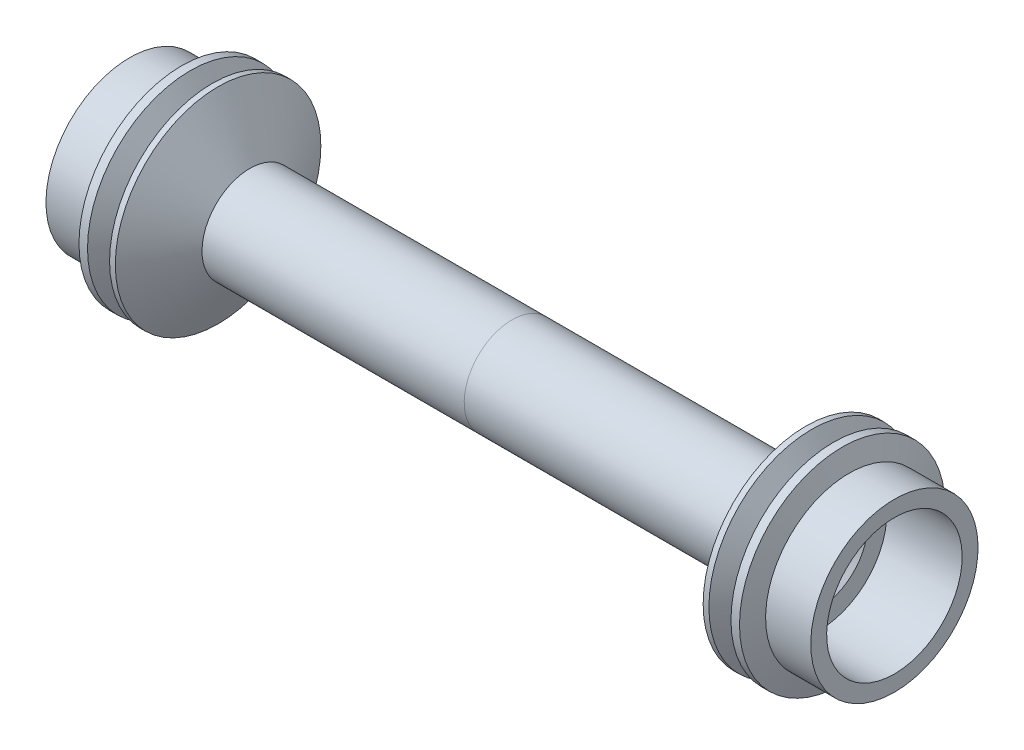
SolidWorks part; units mm, degrees
ref_plane "Front Plane" through (0, 0, 0) normal (0, 0, 1) x (1, 0, 0)
ref_plane "Top Plane" through (0, 0, 0) normal (0, 1, 0) x (1, 0, 0)
ref_plane "Right Plane" through (0, 0, 0) normal (1, 0, 0) x (0, 0, -1)
sketch "Sketch2" plane through (0, 0, 0) normal (0, 0, 1) x (1, 0, 0)
  line L0 (0, 0) -> (0, 28.4375) construction
  line L1 (-25.4, 4.5) -> (-20.4, 4.5) construction
  line L2 (-25.4, 4.5) -> (-25.4, -4.5) construction
  line L3 (-25.4, -4.5) -> (-20.4, -4.5) construction
  line L4 (-20.4, 4.5) -> (-20.4, -4.5) construction
  line L5 (-25.4, 4.5) -> (-20.4, -4.5) construction
  line L6 (-25.4, -4.5) -> (-20.4, 4.5) construction
  line L7 (20.4, 4.5) -> (43.1832, 4.5) construction
  line L8 (20.4, 4.5) -> (20.4, -4.5) construction
  line L9 (20.4, -4.5) -> (43.1832, -4.5) construction
  line L10 (43.1832, 4.5) -> (43.1832, -4.5) construction
  line L11 (20.4, 4.5) -> (43.1832, -4.5) construction
  line L12 (20.4, -4.5) -> (43.1832, 4.5) construction
  line L13 (-25.4, 0) -> (43.1832, 0) construction
  line L14 (-25.4, 5.5562) -> (-22.4, 5.5562)
  line L15 (-22.4, 5.5562) -> (-21.9378, 6.8262)
  line L16 (-21.9378, 6.8262) -> (-21.3707, 6.8262)
  line L17 (-21.3707, 6.8262) -> (-20.6375, 5.5562)
  line L18 (-20.6375, 5.5562) -> (-19.9043, 6.8262)
  line L19 (-19.9043, 6.8262) -> (-19.5233, 6.8262)
  line L20 (-19.5233, 6.8262) -> (-17.4152, 3.175)
  line L21 (-17.4152, 3.175) -> (0, 3.175)
  line L22 (-25.4, 5.5562) -> (-25.4, 4.5)
  line L23 (-25.4, 4.5) -> (-20.4, 4.5)
  line L24 (-20.4, 4.5) -> (-20.4, 0)
  line L25 (-20.4, 0) -> (0, 0)
  line L26 (0, 0) -> (0, 3.175)
  line L27 (-33.5594, -5.5562) -> (-33.5594, 5.5562) construction
  line L28 (-20.6375, 5.5562) -> (-20.6375, 7.68) construction
  line L29 (-20.6375, 5.5562) -> (20.6375, 5.5562) construction
  line L30 (-25.4, 5.5562) -> (25.4, 5.5562) construction
  line L31 (0, 1.6) -> (-12.5, 1.6)
  line L32 (-12.5, 1.6) -> (-14.1, 0)
  line L33 (-12.5, 1.6) -> (-12.5, -1.6) construction
  line L34 (-12.5, 1.6) -> (12.5, 1.6) construction
  line L35 (-20.4, 1.7145) -> (-15.575, 1.7145)
  line L36 (-15.575, 1.7145) -> (-15.575, 0)
  line L37 (-20.4, 3.23) -> (-19.892, 2.722)
  line L38 (-15.575, 1.7145) -> (-28.575, 1.7145) construction
  line L39 (-15.575, 1.7145) -> (-15.575, -1.7145) construction
  line L40 (-15.575, -1.7145) -> (-28.575, -1.7145) construction
  line L41 (-28.575, 1.7145) -> (-28.575, -1.7145) construction
  line L42 (-19.892, 2.722) -> (-19.892, 0)
  point P0 (-22.9, 0)
  point P5 (31.7916, 0)
  point P27 (-33.5594, 0)
  point P28 (-19.7138, 6.8262)
  point P29 (-12.5, 0)
  point P33 (0, 5.5562)
  point P36 (0, 1.6)
  point P48 (-15.575, 0)
  point P51 (0, 5.5562)
  dimension "D1" = 5
  dimension "D3" = 3.175
  dimension "D4" = 11.1125
  dimension "D5" = 9
  dimension "D6" = 60
  dimension "D7" = 60
  dimension "D8" = 1.27
  dimension "D9" = 70
  dimension "D10" = 41.275
  dimension "D11" = 50.8
  dimension "D12" = 0.381
  dimension "D13" = 45
  dimension "D14" = 25
  dimension "D15" = 3.2
  dimension "D16" = 3.429
  dimension "D17" = 3.175
  dimension "D18" = 1.27
  dimension "D19" = 0.508
  dimension "D20" = 45
  dimension "D21" = 13
  dimension "D22" = 3
revolve "Revolve1" add sketch "Sketch2" angle 360 about L13
mirror "Mirror1" about plane through (0, 0, 0) normal (1, 0, 0) of bodies 101
chamfer "Chamfer1" distance 0.508 angle 45 1 edges at (-25.4, -4.5, 0)
